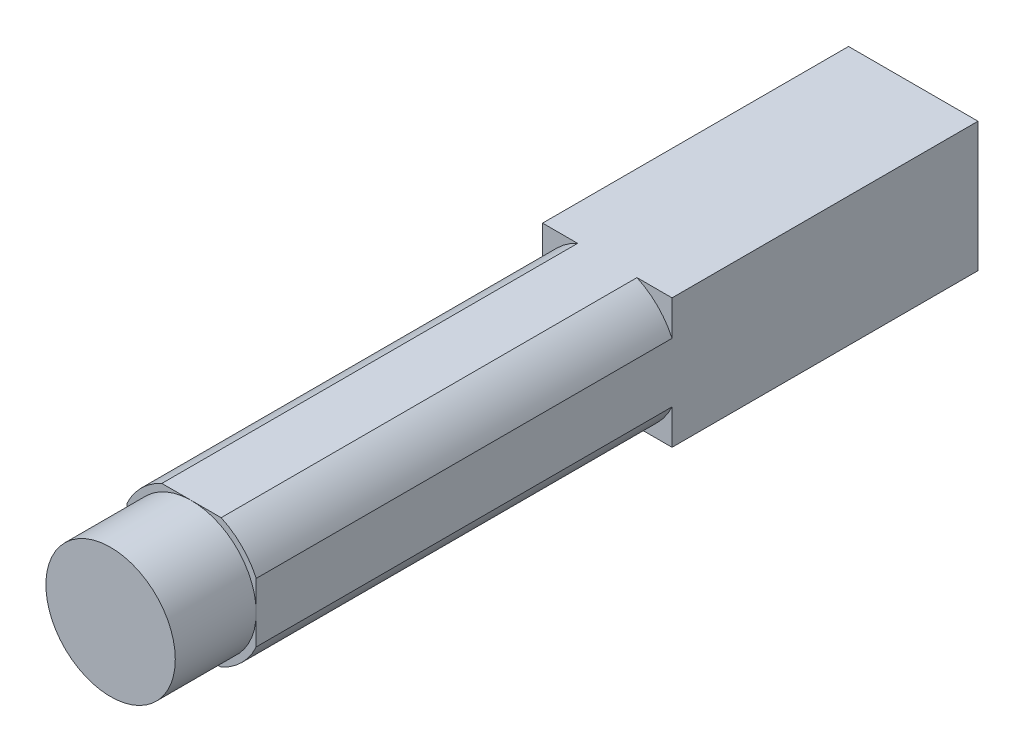
SolidWorks part; units mm, degrees
ref_plane "Front Plane" through (0, 0, 0) normal (0, 0, 1) x (1, 0, 0)
ref_plane "Top Plane" through (0, 0, 0) normal (0, 1, 0) x (1, 0, 0)
ref_plane "Right Plane" through (0, 0, 0) normal (1, 0, 0) x (0, 0, -1)
sketch "Sketch1" plane through (0, 0, 0) normal (0, 0, 1) x (1, 0, 0)
  line L1 (-3.175, 3.175) -> (3.175, 3.175)
  line L2 (-3.175, 3.175) -> (-3.175, -3.175)
  line L3 (-3.175, -3.175) -> (3.175, -3.175)
  line L4 (3.175, 3.175) -> (3.175, -3.175)
  line L5 (-3.175, 3.175) -> (3.175, -3.175) construction
  line L6 (-3.175, -3.175) -> (3.175, 3.175) construction
  point P0 (0, 0)
  dimension "D1" = 6.35
extrude "Boss-Extrude1" add sketch "Sketch1" along normal blind 39.37
sketch "Sketch2" plane through (0, 0, 39.37) normal (0, 0, 1) x (1, 0, 0)
  line L2 (3.175, -3.175) -> (-3.175, -3.175)
  line L3 (3.175, -3.175) -> (3.175, 3.175)
  line L4 (3.175, 3.175) -> (-3.175, 3.175)
  line L5 (-3.175, -3.175) -> (-3.175, 3.175)
  line L6 (3.175, -3.175) -> (-3.175, 3.175) construction
  line L7 (3.175, 3.175) -> (-3.175, -3.175) construction
  circle A0 centre (0, 0) radius 3.1737
  dimension "D1" = 6.3475
extrude "Cut-Extrude1" cut sketch "Sketch2" against normal blind 3.9688
sketch "Sketch3" plane through (0, 0, 35.4013) normal (0, 0, 1) x (1, 0, 0)
  line L1 (4.7625, -4.7625) -> (-4.7625, -4.7625)
  line L2 (4.7625, -4.7625) -> (4.7625, 4.7625)
  line L3 (4.7625, 4.7625) -> (-4.7625, 4.7625)
  line L4 (-4.7625, -4.7625) -> (-4.7625, 4.7625)
  line L5 (4.7625, -4.7625) -> (-4.7625, 4.7625) construction
  line L6 (4.7625, 4.7625) -> (-4.7625, -4.7625) construction
  circle A1 centre (0, 0) radius 3.4925
  dimension "D1" = 9.525
  dimension "D2" = 6.985
extrude "Cut-Extrude2" cut sketch "Sketch3" against normal blind 20.3947
